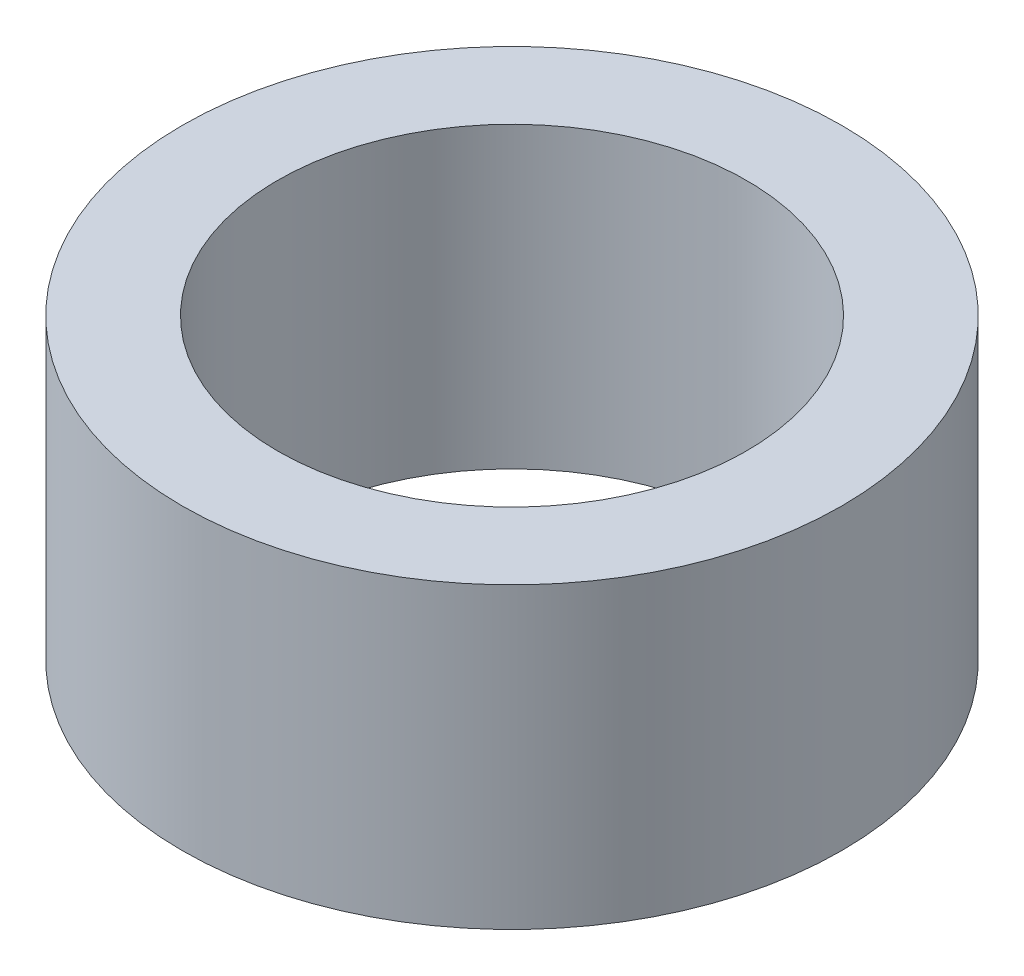
SolidWorks part; units mm, degrees
material "1060 Alloy"
ref_plane "Front Plane" through (0, 0, 0) normal (0, 0, 1) x (1, 0, 0)
ref_plane "Top Plane" through (0, 0, 0) normal (0, 1, 0) x (1, 0, 0)
ref_plane "Right Plane" through (0, 0, 0) normal (1, 0, 0) x (0, 0, -1)
sketch "Sketch1" plane through (0, 0, 0) normal (0, 1, 0) x (1, 0, 0)
  circle A0 centre (0, 0) radius 2.25
  circle A1 centre (0, 0) radius 1.6
  dimension "D1" = 3.2
  dimension "D2" = 4.5
extrude "Boss-Extrude1" add sketch "Sketch1" along normal blind 2.037
equation "\"ID\"=0.003200"
equation "\"OD\"=0.004500"
equation "\"D1@Sketch1\"=\"ID\"*1000"
equation "\"D2@Sketch1\"=\"OD\"*1000"
equation "\"H\"=0.002037"
equation "\"D1@Boss-Extrude1\" = \"H\"*1000"
equation "\"Ha\"=0.003075"
